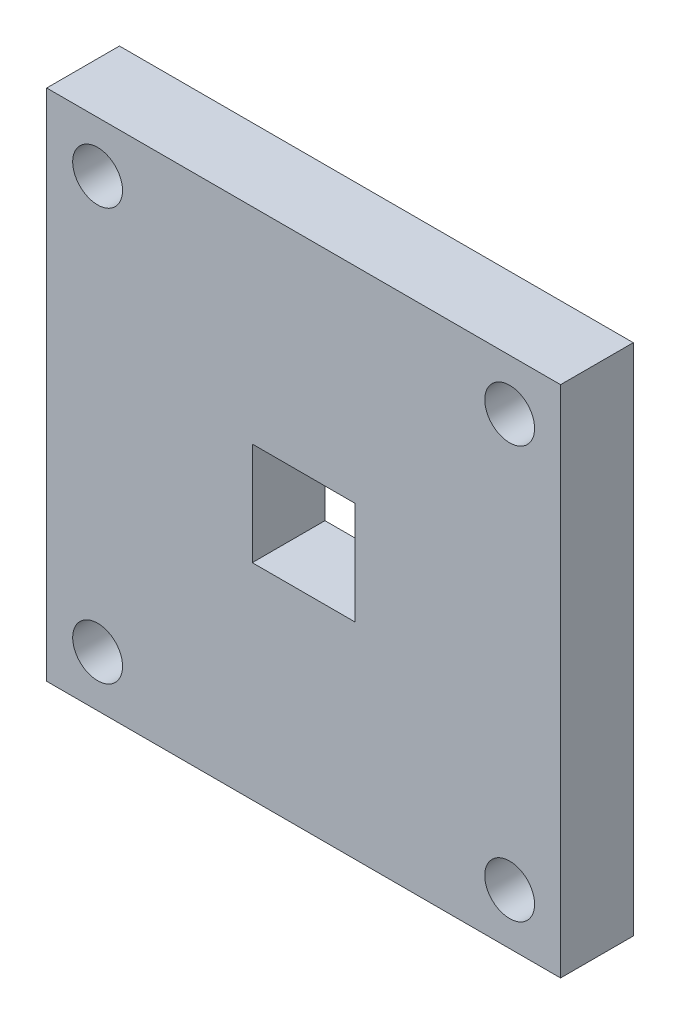
SolidWorks part; units mm, degrees
material "Beech"
ref_plane "Front Plane" through (0, 0, 0) normal (0, 0, 1) x (1, 0, 0)
ref_plane "Top Plane" through (0, 0, 0) normal (0, 1, 0) x (1, 0, 0)
ref_plane "Right Plane" through (0, 0, 0) normal (1, 0, 0) x (0, 0, -1)
sketch "Sketch2" plane through (0, 0, 0) normal (0, 0, 1) x (1, 0, 0)
  line L1 (-16.8275, -16.8275) -> (16.8275, -16.8275)
  line L2 (-16.8275, -16.8275) -> (-16.8275, 16.8275)
  line L3 (-16.8275, 16.8275) -> (16.8275, 16.8275)
  line L4 (16.8275, -16.8275) -> (16.8275, 16.8275)
  line L5 (-16.8275, -16.8275) -> (16.8275, 16.8275) construction
  line L6 (-16.8275, 16.8275) -> (16.8275, -16.8275) construction
  point P0 (0, 0)
  dimension "D1" = 33.655
extrude "Boss-Extrude1" add sketch "Sketch2" along normal mid plane 4.7625
sketch "Sketch3" plane through (0, 0, 2.3813) normal (0, 0, 1) x (1, 0, 0)
  line L1 (-3.3655, -3.3655) -> (3.3655, -3.3655)
  line L2 (-3.3655, -3.3655) -> (-3.3655, 3.3655)
  line L3 (-3.3655, 3.3655) -> (3.3655, 3.3655)
  line L4 (3.3655, -3.3655) -> (3.3655, 3.3655)
  line L5 (-3.3655, -3.3655) -> (3.3655, 3.3655) construction
  line L6 (-3.3655, 3.3655) -> (3.3655, -3.3655) construction
  point P0 (0, 0)
  dimension "D1" = 6.731
extrude "Cut-Extrude1" cut sketch "Sketch3" against normal up to next
hole_wizard "#4 Clearance Hole1" positions "Sketch5" profile "Sketch4" hole size "#4" standard "ANSI Inch"
sketch "Sketch5" plane through (0, 0, 2.3813) normal (0, 0, 1) x (1, 0, 0)
  line L1 (-13.4937, -13.4937) -> (13.4937, -13.4937) construction
  line L2 (-13.4937, -13.4937) -> (-13.4937, 13.4937) construction
  line L3 (-13.4937, 13.4937) -> (13.4937, 13.4937) construction
  line L4 (13.4937, -13.4937) -> (13.4937, 13.4937) construction
  line L5 (-13.4937, -13.4937) -> (13.4937, 13.4937) construction
  line L6 (-13.4937, 13.4937) -> (13.4937, -13.4937) construction
  point P0 (-13.4937, 13.4937)
  point P4 (0, 0)
  point P5 (13.4937, 13.4937)
  point P228 (-13.4937, -13.4937)
  point P230 (13.4937, -13.4937)
  dimension "D1" = 26.9875
sketch "Sketch4" plane through (-13.4937, 13.4937, 2.3813) normal (1, 0, 0) x (0, -1, 0)
  line L0 (0, 0) -> (0, 9.8706)
  line L1 (0, 9.8706) -> (1.6319, 8.89)
  line L2 (1.6319, 8.89) -> (1.6319, 0)
  line L5 (1.6319, 0) -> (0, 0)
  line L10 (0, 9.8706) -> (-1.632, 8.89) construction
  line L11 (0, -6.35) -> (0, 107.95) construction
  dimension "Hole Dia." = 3.2639
  dimension "Hole Depth" = 8.89
  dimension "Drill Angle" = 118
